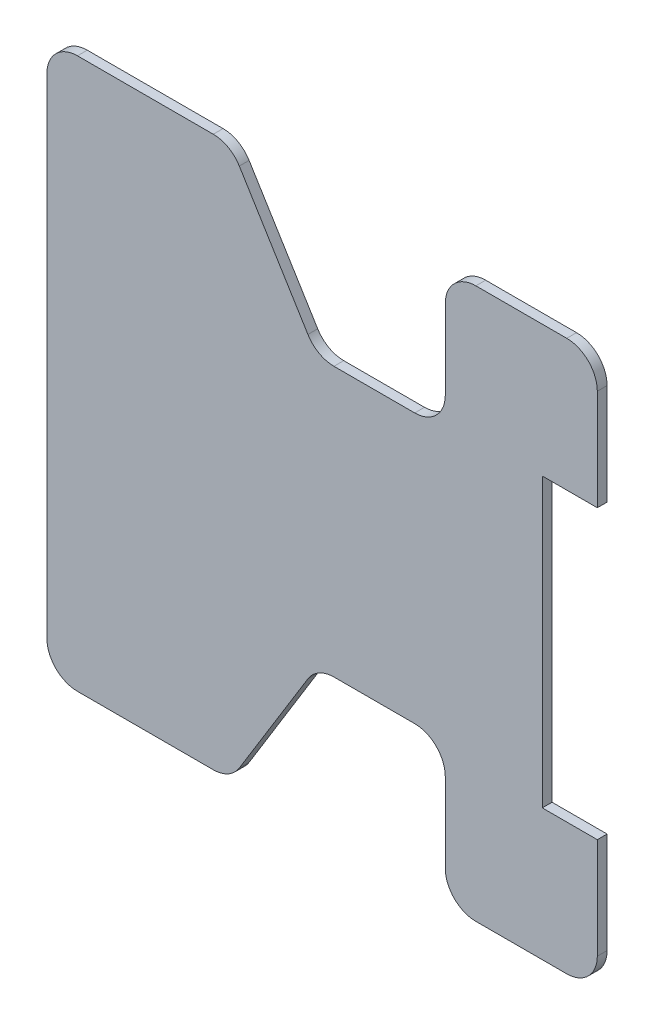
SolidWorks part; units mm, degrees
ref_plane "Front Plane" through (0, 0, 0) normal (0, 0, 1) x (1, 0, 0)
ref_plane "Top Plane" through (0, 0, 0) normal (0, 1, 0) x (1, 0, 0)
ref_plane "Right Plane" through (0, 0, 0) normal (1, 0, 0) x (0, 0, -1)
sketch "Sketch1" plane through (0, 0, 0) normal (0, 0, 1) x (1, 0, 0)
  line L0 (90, 68.5) -> (90, 90)
  line L1 (0, 0) -> (90, 0)
  line L2 (0, 0) -> (0, 90)
  line L3 (0, 90) -> (90, 90)
  line L4 (90, 0) -> (90, 21.5)
  line L5 (90, 68.5) -> (81, 68.5)
  line L7 (90, 21.5) -> (81, 21.5)
  line L8 (81, 68.5) -> (81, 21.5)
  point P9 (81, 45)
  point P10 (0, 0)
  point P11 (0, 45)
  dimension "D1" = 90
  dimension "D2" = 90
  dimension "D3" = 9
  dimension "D4" = 47
extrude "Boss-Extrude1" add sketch "Sketch1" along normal blind 1.6
sketch "Sketch2" plane through (0, 0, 1.6) normal (0, 0, 1) x (1, 0, 0)
  line L0 (0, 90) -> (30, 90)
  line L1 (90, 90) -> (0, 90) construction
  line L2 (30, 90) -> (44.1421, 67)
  line L3 (44.1421, 67) -> (65.1421, 67)
  line L4 (65.1421, 67) -> (65.1421, 90)
  line L5 (65.1421, 90) -> (90, 90)
  line L6 (90, 90) -> (90, 68.5)
  line L7 (90, 68.5) -> (81, 68.5)
  line L8 (81, 68.5) -> (81, 21.5)
  line L9 (81, 21.5) -> (90, 21.5)
  line L10 (90, 21.5) -> (90, 0)
  line L11 (90, 0) -> (65.1421, 0)
  line L12 (0, 0) -> (90, 0) construction
  line L13 (65.1421, 0) -> (65.1421, 23)
  line L14 (65.1421, 23) -> (44.1421, 23)
  line L15 (44.1421, 23) -> (30, 0)
  line L16 (30, 0) -> (0, 0)
  line L17 (0, 0) -> (0, 90)
  dimension "D1" = 27
  dimension "D2" = 27
  dimension "D3" = 21
  dimension "D4" = 23
  dimension "D5" = 23
  dimension "D6" = 21
  dimension "D7" = 30
  dimension "D8" = 30
  dimension "D9" = 24.8579
  dimension "D10" = 24.8579
extrude "Cut-Extrude1" cut sketch "Sketch2" against normal through all flip side to cut
fillet "Fillet2" radius 5 12 edges at (0, 90, 0.8) (0, 0, 0.8) (30, 0, 0.8) (30, 90, 0.8) (90, 90, 0.8) (90, 0, 0.8) (44.1421, 67, 0.8) (44.1421, 23, 0.8) (65.1421, 0, 0.8) (65.1421, 23, 0.8) (65.1421, 67, 0.8) (65.1421, 90, 0.8)
